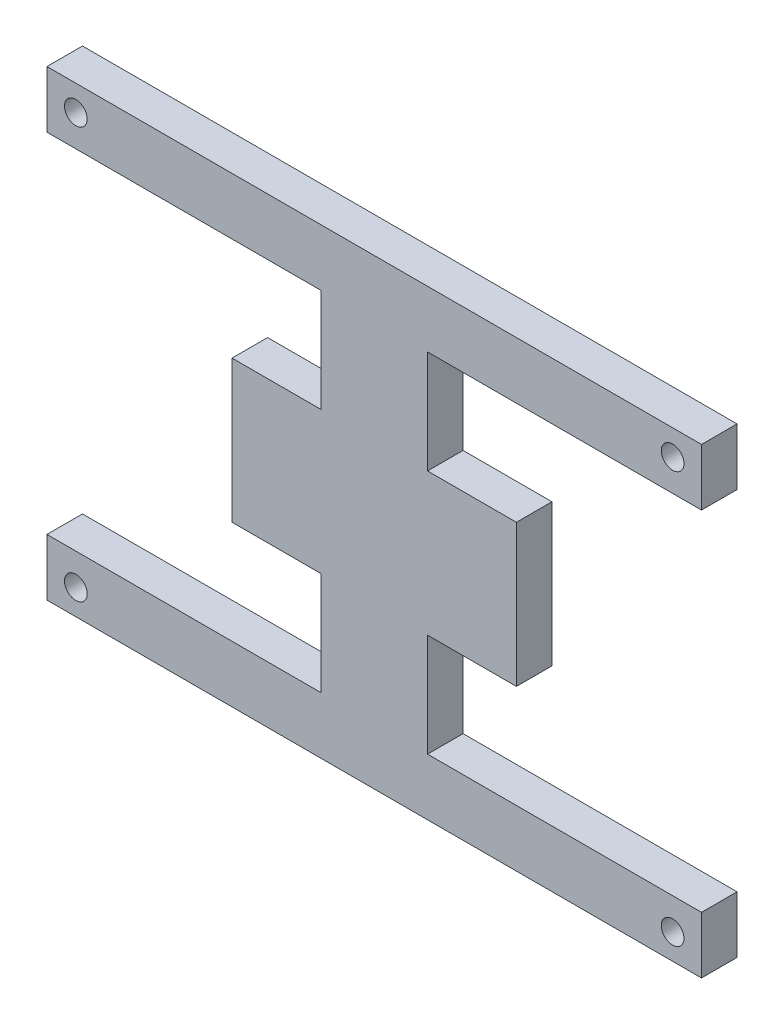
SolidWorks part; units mm, degrees
ref_plane "前视基准面" through (0, 0, 0) normal (0, 0, 1) x (1, 0, 0)
ref_plane "上视基准面" through (0, 0, 0) normal (0, 1, 0) x (1, 0, 0)
ref_plane "右视基准面" through (0, 0, 0) normal (1, 0, 0) x (0, 0, -1)
other "Configuration Table"
sketch "草图1" plane through (0, 0, 0) normal (0, 0, 1) x (1, 0, 0)
  line L0 (46.0375, -32.5) -> (46.0375, 32.5) construction
  line L1 (-46.0375, 32.5) -> (46.0375, 32.5)
  line L2 (-46.0375, 32.5) -> (-46.0375, 24.5)
  line L3 (-46.0375, 24.5) -> (46.0375, 24.5)
  line L4 (46.0375, 32.5) -> (46.0375, 24.5)
  line L5 (-46.0375, -32.5) -> (-46.0375, 32.5) construction
  line L6 (46.0375, -32.5) -> (-46.0375, -32.5)
  line L7 (46.0375, -32.5) -> (46.0375, -24.5)
  line L8 (46.0375, -24.5) -> (-46.0375, -24.5)
  line L9 (-46.0375, -32.5) -> (-46.0375, -24.5)
  line L10 (0, 24.5) -> (0, -24.5) construction
  line L15 (-7.5, 0) -> (7.5, 0) construction
  line L16 (-7.5, -24.5) -> (7.5, -24.5)
  line L17 (-7.5, -24.5) -> (-7.5, 24.5)
  line L18 (-7.5, 24.5) -> (7.5, 24.5)
  line L19 (7.5, -24.5) -> (7.5, 24.5)
  line L20 (-7.5, -24.5) -> (7.5, 24.5) construction
  line L21 (-7.5, 24.5) -> (7.5, -24.5) construction
  line L23 (-20, -10) -> (20, -10)
  line L24 (-20, -10) -> (-20, 10)
  line L25 (-20, 10) -> (20, 10)
  line L26 (20, -10) -> (20, 10)
  line L27 (-20, -10) -> (20, 10) construction
  line L28 (-20, 10) -> (20, -10) construction
  circle A0 centre (-41.9735, 28.92) radius 1.6
  circle A1 centre (41.9735, 28.92) radius 1.6
  circle A2 centre (41.9735, -28.92) radius 1.6
  circle A3 centre (-41.9735, -28.92) radius 1.6
  point P28 (0, 0)
  point P36 (0, 0)
  dimension "D3" = 3.2
  dimension "D4" = 3.2
  dimension "D5" = 3.2
  dimension "D6" = 3.2
  dimension "D1" = 8
  dimension "D2" = 8
  dimension "D7" = 15
  dimension "D8" = 20
  dimension "D9" = 40
extrude "凸台-拉伸1" add sketch "草图1" along normal blind 5 contours L4 L1 L2 L3 A1 A0 | L23 L26 L25 L19 | L25 L17 L23 L19 | L25 L24 L23 L17 | L17 L25 L19 L3 | L9 L6 L7 L8 A3 A2 | L23 L17 L8 L19
